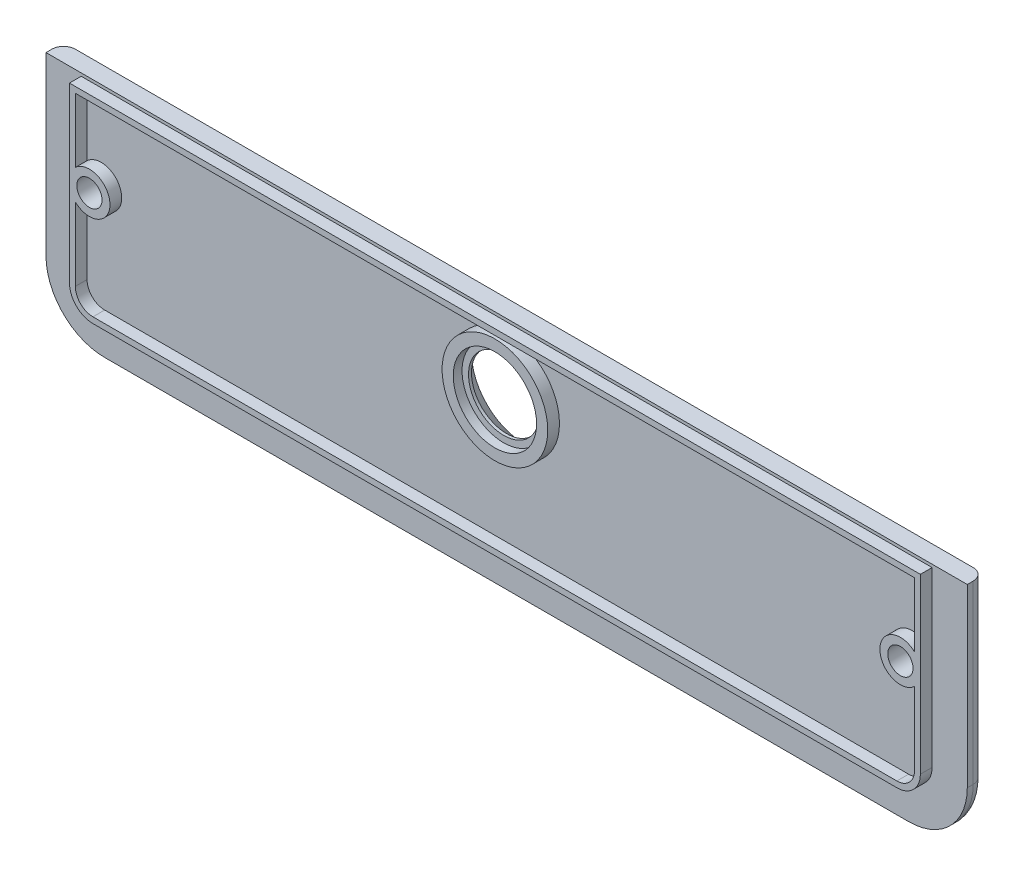
SolidWorks part; units mm, degrees
ref_plane "Front Plane" through (0, 0, 0) normal (0, 0, 1) x (1, 0, 0)
ref_plane "Top Plane" through (0, 0, 0) normal (0, 1, 0) x (1, 0, 0)
ref_plane "Right Plane" through (0, 0, 0) normal (1, 0, 0) x (0, 0, -1)
sketch "Sketch1" plane through (0, 0, 0) normal (0, 0, 1) x (1, 0, 0)
  line L0 (0, 35.5) -> (147, 35.5)
  line L1 (5, 0) -> (142, 0)
  line L2 (0, 5) -> (0, 55.5)
  line L3 (0, 55.5) -> (147, 55.5)
  line L4 (147, 5) -> (147, 55.5)
  line L5 (0, 42.5) -> (147, 42.5)
  line L6 (73.5, 0) -> (73.5, 55.5) construction
  line L7 (63.5, 0) -> (63.5, 35.5) construction
  arc A0 (142, 0) -> (147, 5) centre (142, 5) ccw
  arc A1 (5, 0) -> (0, 5) centre (5, 5) cw
  circle A2 centre (4.4, 17.75) radius 1.75
  circle A3 centre (142.6, 17.75) radius 1.75
  point P11 (147, 0)
  point P14 (0, 0)
  point P24 (63.5, 17.75)
  dimension "D5" = 5
  dimension "D6" = 3.5
  dimension "D1" = 147
  dimension "D2" = 55.5
  dimension "D3" = 35.5
  dimension "D4" = 42.5
  dimension "D7" = 138.2
  dimension "D8" = 10
sketch "Sketch2" plane through (0, 0, 0) normal (0, 0, 1) x (1, 0, 0)
  line L17 (-5, 35) -> (152, 35)
  line L18 (0, 35.5) -> (147, 35.5) construction
  line L21 (152, 60.5) -> (-5, 60.5)
  line L22 (152, 5) -> (152, 60.5)
  line L23 (-5, 60.5) -> (-5, 5)
  line L24 (5, -5) -> (142, -5)
  line L26 (152, 5) -> (152, 35)
  line L27 (-5, 35) -> (-5, 5)
  line L28 (5, -5) -> (142, -5)
  arc A10 (-5, 5) -> (5, -5) centre (5, 5) ccw
  arc A11 (142, -5) -> (152, 5) centre (142, 5) ccw
  arc A12 (-5, 5) -> (5, -5) centre (5, 5) ccw
  arc A13 (142, -5) -> (152, 5) centre (142, 5) ccw
  dimension "D2" = 0.5
  dimension "D1" = 5
extrude "Boss-Base" add sketch "Sketch2" along normal blind 3
sketch "Sketch3" plane through (0, 0, 3) normal (0, 0, 1) x (1, 0, 0)
  line L0 (152, 35) -> (-5, 35) construction
  line L5 (1, 5) -> (1, 34.5)
  line L6 (1, 34.5) -> (146, 34.5)
  line L7 (2, 33.5) -> (145, 33.5)
  line L8 (146, 34.5) -> (146, 5)
  line L9 (142, 1) -> (5, 1)
  line L10 (145, 55.5) -> (145, 5)
  line L11 (2, 5) -> (2, 55.5)
  line L12 (142, 2) -> (5, 2)
  line L14 (2, 5) -> (2, 17.4525)
  line L15 (142, 2) -> (5, 2)
  line L16 (2, 22.5475) -> (2, 33.5)
  line L17 (2, 5) -> (2, 33.5) construction
  line L18 (73.5, 0) -> (73.5, 55.5) construction
  line L19 (145, 33.5) -> (145, 5) construction
  line L20 (73.5, 0) -> (73.5, 55.5) construction
  line L21 (145, 22.5475) -> (145, 33.5)
  line L22 (145, 5) -> (145, 17.4525)
  arc A0 (142, 1) -> (146, 5) centre (142, 5) ccw
  arc A1 (1, 5) -> (5, 1) centre (5, 5) ccw
  arc A4 (142, 2) -> (145, 5) centre (142, 5) ccw
  arc A5 (2, 5) -> (5, 2) centre (5, 5) ccw
  arc A6 (142, 2) -> (145, 5) centre (142, 5) ccw
  arc A7 (2, 5) -> (5, 2) centre (5, 5) ccw
  circle A8 centre (4.4, 20) radius 2.15
  arc A10 (2, 17.4525) -> (2, 22.5475) centre (4.4, 20) ccw
  arc A11 (145, 17.4525) -> (145, 22.5475) centre (142.6, 20) cw
  circle A12 centre (142.6, 20) radius 2.15
  dimension "D4" = 4.3
  dimension "D5" = 7
  dimension "D7" = 4.3
  dimension "D2" = 1.5
  dimension "D6" = 20
  dimension "D1" = 2
  dimension "D3" = 1
extrude "Boss-Fit" add sketch "Sketch3" along normal blind 2
sketch "Sketch4" plane through (0, 0, 3) normal (0, 0, 1) x (1, 0, 0)
  circle A0 centre (4.4, 20) radius 2.15 construction
  circle A1 centre (4.4, 20) radius 2.15
  circle A2 centre (142.6, 20) radius 2.15 construction
  circle A3 centre (142.6, 20) radius 2.15
extrude "Cut-Screws" cut sketch "Sketch4" against normal offset from surface (2 mm away) 1 up to face at (73.5, 10.9763, 0)
fillet "Fillet1" radius 2 5 edges at (-5, 20, 0) (-2.0711, -2.0711, 0) (152, 20, 0) (149.0711, -2.0711, 0) (73.5, -5, 0)
sketch "Sketch10" plane through (0, 0, 0) normal (0, 0, -1) x (-1, 0, 0)
  line L0 (-140.7988, 14) -> (-145, 8)
  line L7 (-145, 8) -> (-142.25, 8)
  line L8 (-142.25, 8) -> (-138.0488, 14)
  line L9 (-138.0488, 14) -> (-140.7988, 14)
  line L10 (-136.0488, 14) -> (-144.4512, 2)
  line L11 (-144.4512, 2) -> (-141.7012, 2)
  line L12 (-141.7012, 2) -> (-133.2988, 14)
  line L13 (-133.2988, 14) -> (-136.0488, 14)
  line L14 (-135.5, 8) -> (-139.7012, 2)
  line L15 (-139.7012, 2) -> (-136.9512, 2)
  line L16 (-136.9512, 2) -> (-132.75, 8)
  line L17 (-132.75, 8) -> (-135.5, 8)
  line L18 (-142, -3) -> (-5, -3) construction
  line L19 (-150, 35) -> (-150, 5) construction
  dimension "D1" = 12
  dimension "D2" = 6
  dimension "D3" = 2.75
  dimension "D4" = 2
  dimension "D5" = 2
  dimension "D6" = 55
  dimension "D7" = 5
  dimension "D8" = 5
extrude "Cut-Voron" cut sketch "Sketch10" against normal blind 0.6
sketch "Sketch8" plane through (0, 0, 3) normal (0, 0, 1) x (1, 0, 0)
  line L0 (73.5, 2) -> (73.5, 54.9904) construction
  line L1 (5, 2) -> (142, 2) construction
  circle A0 centre (73.5, 24) radius 9
  dimension "D2" = 18
  dimension "D1" = 24
extrude "Boss-Bearing" add sketch "Sketch8" along normal blind 2 contours A0
sketch "Sketch12" plane through (0, 0, 5) normal (0, 0, 1) x (1, 0, 0)
  circle A0 centre (73.5, 24) radius 7.1
  dimension "D1" = 14.2
extrude "Cut-Bearing1" cut sketch "Sketch12" against normal blind 1.5
sketch "Sketch11" plane through (0, 0, 5) normal (0, 0, 1) x (1, 0, 0)
  circle A0 centre (73.5, 24) radius 6
  circle A1 centre (73.5, 24) radius 9 construction
  dimension "D1" = 12
extrude "Cut-Bearing2" cut sketch "Sketch11" against normal through all
chamfer "Chamfer2" distance 3 angle 45 1 edges at (79.5, 24, 0)
equation "\"width\"=147"
equation "\"D1@Sketch1\"=\"width\""
equation "\"height\"=42.5"
equation "\"height_outside\"=55.5"
equation "\"D2@Sketch1\"=\"height_outside\""
equation "\"height_inside\"=35.5"
equation "\"D3@Sketch1\"=\"height_inside\""
equation "\"D4@Sketch1\"=\"height\""
